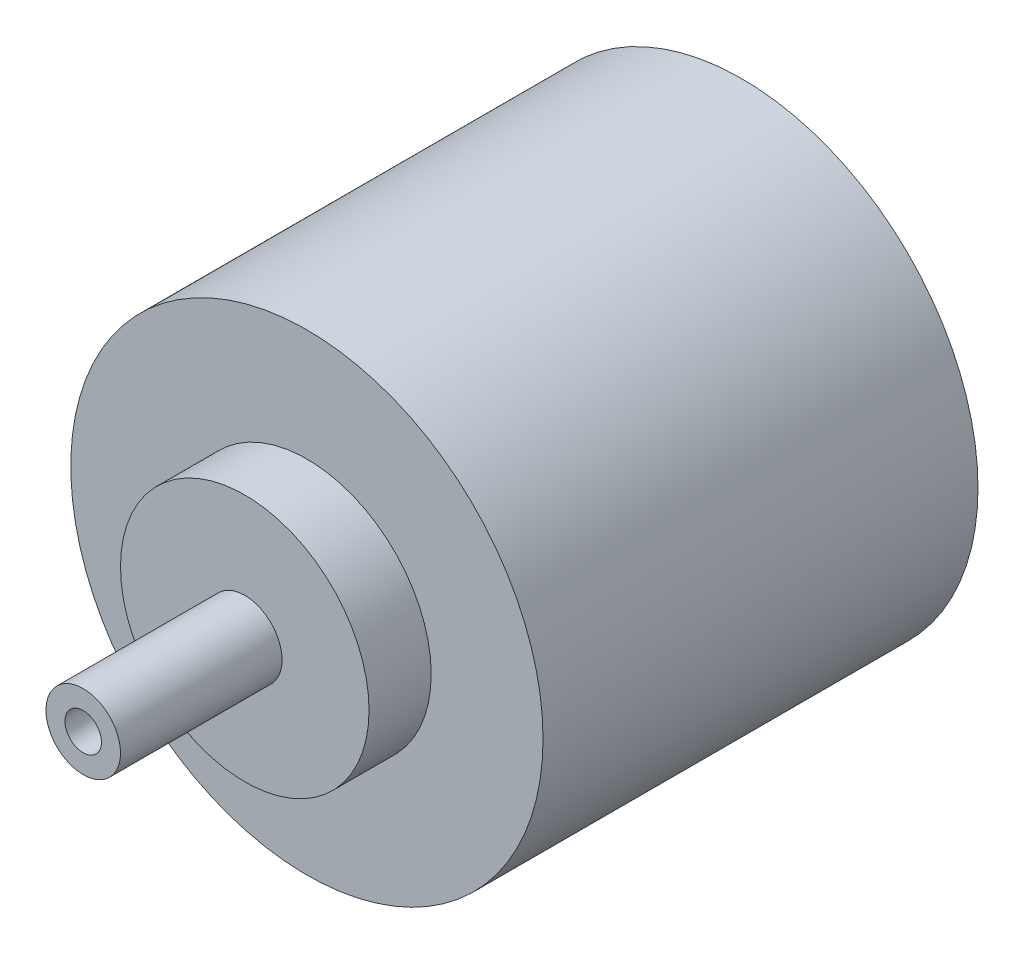
SolidWorks part; units mm, degrees
ref_plane "Front Plane" through (0, 0, 0) normal (0, 0, 1) x (1, 0, 0)
ref_plane "Top Plane" through (0, 0, 0) normal (0, 1, 0) x (1, 0, 0)
ref_plane "Right Plane" through (0, 0, 0) normal (1, 0, 0) x (0, 0, -1)
sketch "Sketch1" plane through (0, 0, 0) normal (1, 0, 0) x (0, 0, -1)
  line L0 (16.2496, 0) -> (88.6301, 0) construction
  line L1 (0, 1.471) -> (0, 3)
  line L2 (0, 3) -> (13, 3)
  line L3 (13, 3) -> (13, 10)
  line L4 (13, 10) -> (18, 10)
  line L5 (18, 10) -> (18, 19)
  line L6 (18, 19) -> (53, 19)
  line L7 (53, 19) -> (53, 0)
  line L8 (53, 0) -> (16.2496, 0)
  line L12 (0, 1.471) -> (16.2496, 1.471)
  line L13 (16.2496, 0) -> (16.2496, 1.471)
  dimension "D1" = 19
  dimension "D2" = 35
  dimension "D3" = 5
  dimension "D4" = 13
  dimension "D5" = 7
revolve "Revolve1" add sketch "Sketch1" angle 360 about L0
